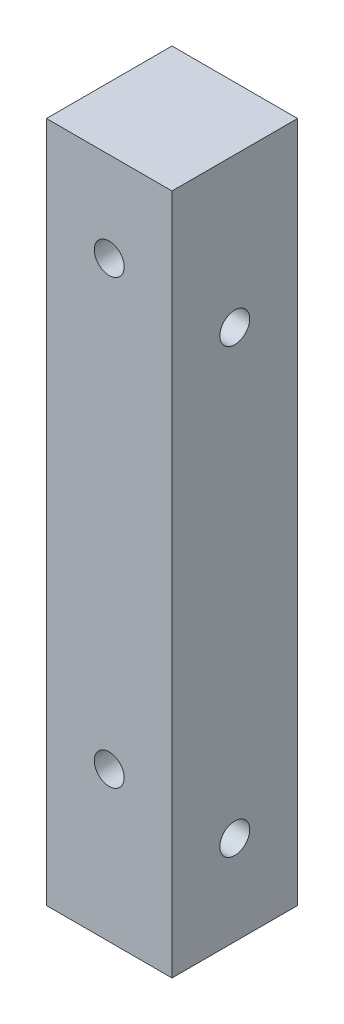
SolidWorks part; units mm, degrees
ref_plane "Front Plane" through (0, 0, 0) normal (0, 0, 1) x (1, 0, 0)
ref_plane "Top Plane" through (0, 0, 0) normal (0, 1, 0) x (1, 0, 0)
ref_plane "Right Plane" through (0, 0, 0) normal (1, 0, 0) x (0, 0, -1)
sketch "Sketch1" plane through (0, 0, 0) normal (0, 1, 0) x (1, 0, 0)
  line L1 (-10.5, -10.5) -> (10.5, -10.5)
  line L2 (-10.5, -10.5) -> (-10.5, 10.5)
  line L3 (-10.5, 10.5) -> (10.5, 10.5)
  line L4 (10.5, -10.5) -> (10.5, 10.5)
  line L5 (-10.5, -10.5) -> (10.5, 10.5) construction
  line L6 (-10.5, 10.5) -> (10.5, -10.5) construction
  point P0 (0, 0)
  dimension "D1" = 21
  dimension "D2" = 21
extrude "Boss-Extrude1" add sketch "Sketch1" along normal blind 114
sketch "Sketch3" plane through (0, 0, 10.5) normal (0, 0, 1) x (1, 0, 0)
  line L0 (-10.5, 114) -> (10.5, 114) construction
  line L1 (-10.5, 0) -> (10.5, 0) construction
  circle A0 centre (0, 99) radius 2.5
  circle A1 centre (0, 25) radius 2.5
  dimension "D1" = 5
  dimension "D2" = 5
  dimension "D4" = 25
  dimension "D3" = 15
extrude "Cut-Extrude1" cut sketch "Sketch3" against normal through all
sketch "Sketch4" plane through (10.5, 0, 0) normal (1, 0, 0) x (0, 0, -1)
  line L0 (-10.5, 0) -> (10.5, 0) construction
  line L1 (-10.5, 114) -> (10.5, 114) construction
  circle A0 centre (0, 89) radius 2.5
  circle A1 centre (0, 15) radius 2.5
  dimension "D1" = 5
  dimension "D2" = 5
  dimension "D3" = 15
  dimension "D4" = 25
extrude "Cut-Extrude2" cut sketch "Sketch4" against normal through all
